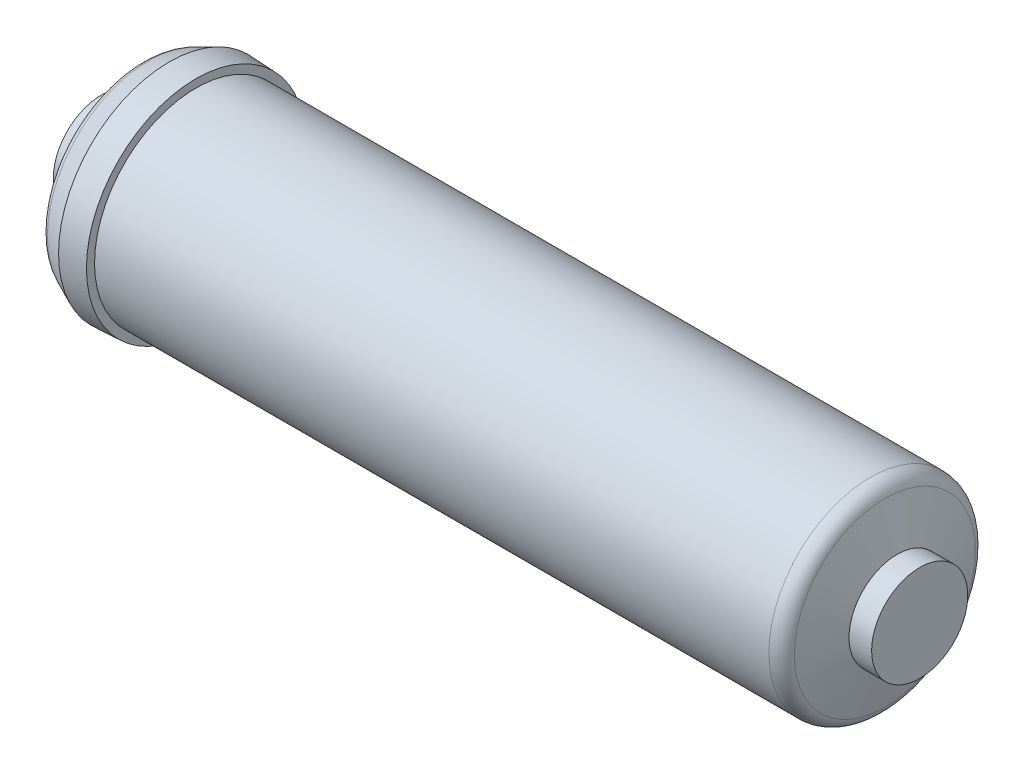
SolidWorks part; units mm, degrees
ref_plane "Front Plane" through (0, 0, 0) normal (0, 0, 1) x (1, 0, 0)
ref_plane "Top Plane" through (0, 0, 0) normal (0, 1, 0) x (1, 0, 0)
ref_plane "Right Plane" through (0, 0, 0) normal (1, 0, 0) x (0, 0, -1)
sketch "Sketch1" plane through (0, 0, 0) normal (0, 0, 1) x (1, 0, 0)
  line L1 (257.175, 0) -> (257.175, 15.113)
  line L2 (257.175, 15.113) -> (250.063, 15.113)
  line L3 (250.063, 15.113) -> (245.237, 31.877)
  line L4 (245.237, 31.877) -> (29.718, 31.877)
  line L5 (29.718, 31.877) -> (29.718, 34.417)
  line L6 (29.718, 34.417) -> (21.336, 34.798)
  line L7 (21.336, 34.798) -> (12.954, 30.988)
  line L8 (12.954, 30.988) -> (7.9502, 15.113)
  line L9 (7.9502, 15.113) -> (0, 15.113)
  line L10 (0, 15.113) -> (0, 0)
  line L11 (0, 0) -> (257.175, 0) construction
  line L12 (0, 0) -> (257.175, 0)
  dimension "D1" = 257.175
  dimension "D2" = 30.226
  dimension "D3" = 7.9502
  dimension "D4" = 7.112
  dimension "D5" = 69.596
  dimension "D6" = 29.718
  dimension "D7" = 63.754
  dimension "D8" = 2.54
  dimension "D9" = 8.382
  dimension "D10" = 8.382
  dimension "D11" = 61.976
  dimension "D12" = 11.938
revolve "Revolve1" add sketch "Sketch1" angle 360 about L11
fillet "Fillet1" radius 4.7625 2 edges at (12.954, 0, 30.988) (245.237, 0, 31.877)
